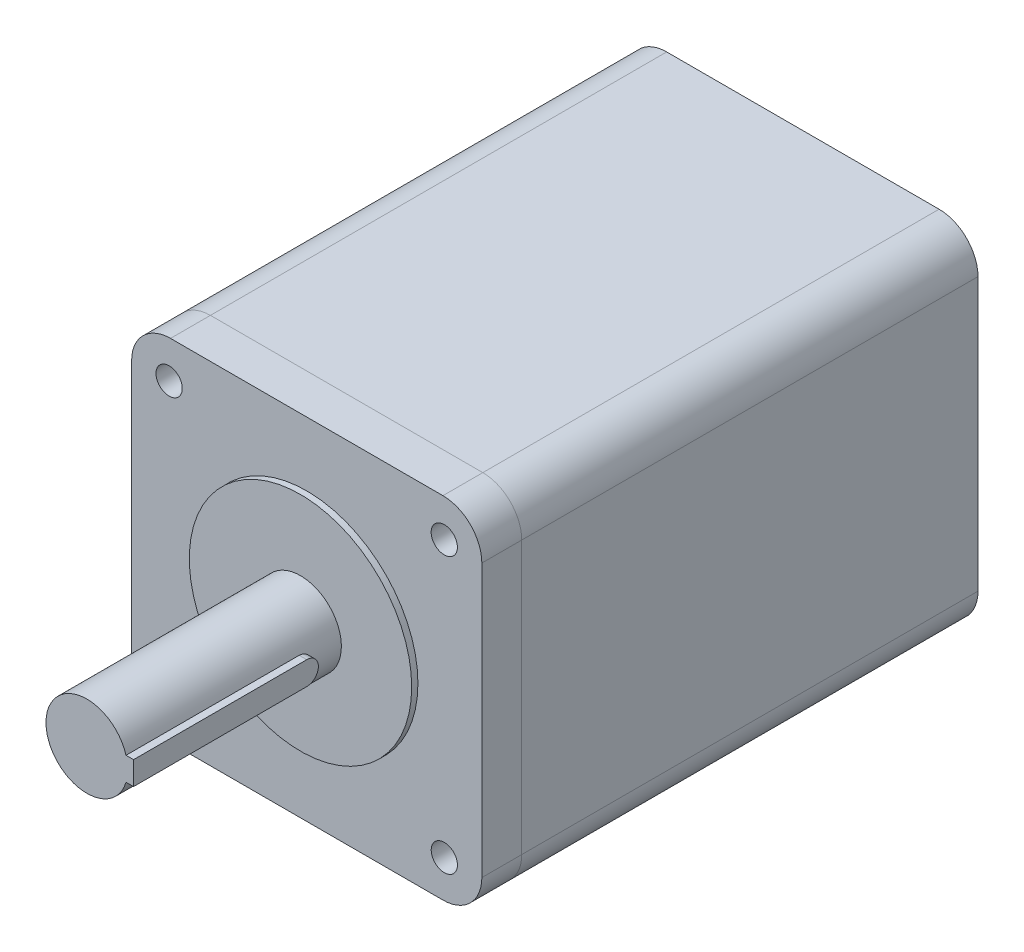
SolidWorks part; units mm, degrees
ref_plane "前视基准面" through (0, 0, 0) normal (0, 0, 1) x (1, 0, 0)
ref_plane "上视基准面" through (0, 0, 0) normal (0, 1, 0) x (1, 0, 0)
ref_plane "右视基准面" through (0, 0, 0) normal (1, 0, 0) x (0, 0, -1)
other "Configuration Table"
sketch "草图1" plane through (0, 0, 0) normal (0, 0, 1) x (1, 0, 0)
  line L1 (-70, -90) -> (70, -90)
  line L2 (-90, -70) -> (-90, 70)
  line L3 (-70, 90) -> (70, 90)
  line L4 (90, -70) -> (90, 70)
  line L5 (-90, -90) -> (90, 90) construction
  line L6 (-90, 90) -> (90, -90) construction
  arc A0 (70, -90) -> (90, -70) centre (70, -70) ccw
  arc A1 (90, 70) -> (70, 90) centre (70, 70) ccw
  arc A2 (-70, -90) -> (-90, -70) centre (-70, -70) cw
  arc A3 (-70, 90) -> (-90, 70) centre (-70, 70) ccw
  point P0 (0, 0)
  dimension "D3" = 20
  dimension "D1" = 180
  dimension "D2" = 180
extrude "凸台-拉伸1" add sketch "草图1" along normal blind 20.5
sketch "草图2" plane through (0, 0, 20.5) normal (0, 0, 1) x (1, 0, 0)
  line L0 (-70, 70) -> (-70.7275, 70.6939) construction
  circle A1 centre (0, 0) radius 100 construction
  circle A2 centre (-70.7275, 70.6939) radius 6.75
  circle A3 centre (70.6939, 70.7275) radius 6.75
  circle A4 centre (70.7275, -70.6939) radius 6.75
  circle A5 centre (-70.6939, -70.7275) radius 6.75
  point P6 (-70, 70)
  point P17 (0, 0)
  dimension "D1" = 1.0053
  dimension "D3" = 4
  dimension "D2" = 13.5
extrude "切除-拉伸1" cut sketch "草图2" against normal up to next
sketch "草图3" plane through (0, 0, 0) normal (0, 0, -1) x (-1, 0, 0)
  line L1 (-70, -90) -> (70, -90)
  line L2 (-90, -70) -> (-90, 70)
  line L3 (-70, 90) -> (70, 90)
  line L4 (90, -70) -> (90, 70)
  line L5 (-90, -90) -> (90, 90) construction
  line L6 (-90, 90) -> (90, -90) construction
  arc A0 (90, -70) -> (70, -90) centre (70, -70) cw
  arc A1 (-70, -90) -> (-90, -70) centre (-70, -70) cw
  arc A2 (90, 70) -> (70, 90) centre (70, 70) ccw
  arc A3 (-70, 90) -> (-90, 70) centre (-70, 70) ccw
  point P0 (0, 0)
  dimension "D1" = 20
extrude "凸台-拉伸2" add sketch "草图3" along normal blind 234.5 separate body
sketch "草图4" plane through (0, 0, 20.5) normal (0, 0, 1) x (1, 0, 0)
  circle A0 centre (0, 0) radius 57.15
  dimension "D1" = 114.3
extrude "凸台-拉伸3" add sketch "草图4" along normal blind 3.2
sketch "草图5" plane through (0, 0, 23.7) normal (0, 0, 1) x (1, 0, 0)
  circle A0 centre (0, 0) radius 21
  dimension "D1" = 42
extrude "凸台-拉伸4" add sketch "草图5" along normal blind 109.8
sketch "草图6" plane through (0, 0, 133.5) normal (0, 0, 1) x (1, 0, 0)
  line L0 (-24.924, 0) -> (35.9707, 0) construction
  line L1 (24, 6) -> (16, 6)
  line L2 (24, 6) -> (24, -6)
  line L3 (24, -6) -> (16, -6)
  line L4 (16, 6) -> (16, -6)
  point P5 (16, 0)
  dimension "D1" = 8
  dimension "D2" = 12
  dimension "D3" = 6
  dimension "D4" = 16
extrude "凸台-拉伸5" add sketch "草图6" against normal blind 89
ref_plane "基准面1" through (24, 0, 0) normal (1, 0, 0) x (0, 0, -1)
sketch "草图7" plane through (24, 0, 0) normal (1, 0, 0) x (0, 0, -1)
  line L0 (-44.5, -6) -> (-44.5, 6)
  arc A0 (-44.5, 6) -> (-44.5, -6) centre (-44.5, 0) cw
  dimension "D1" = 6
extrude "凸台-拉伸6" add sketch "草图7" against normal up to next
